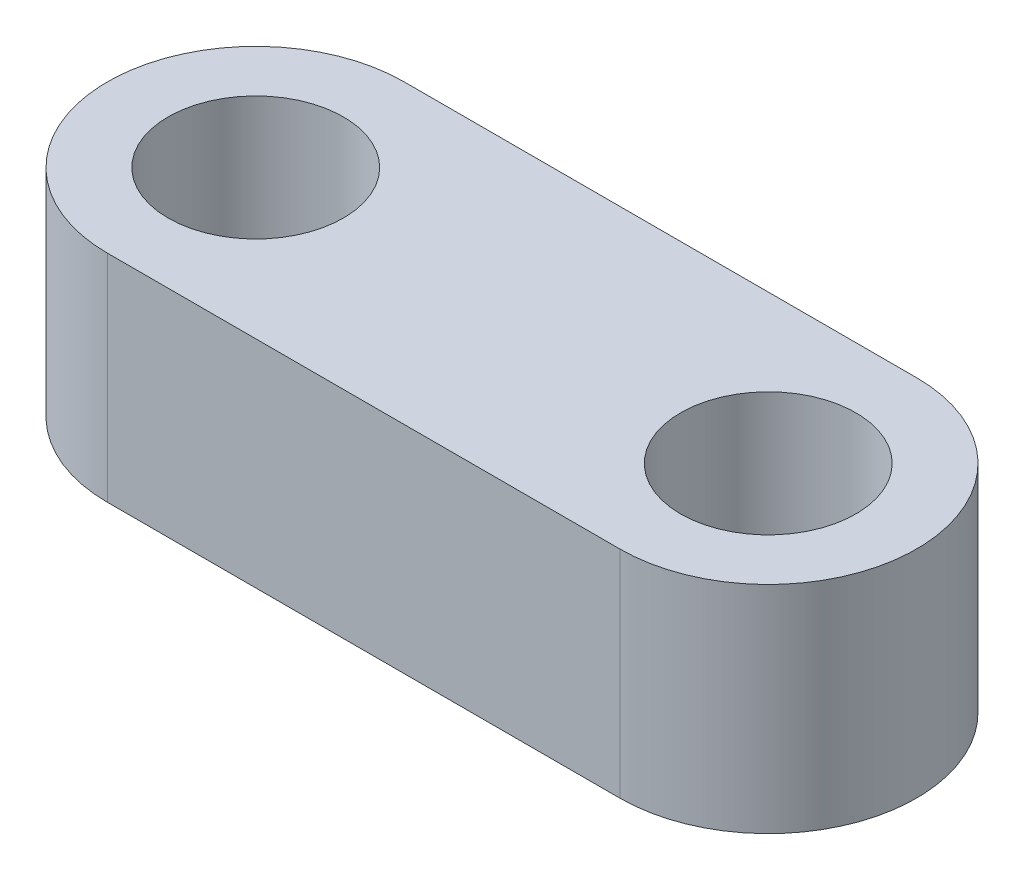
SolidWorks part; units mm, degrees
ref_plane "Front Plane" through (0, 0, 0) normal (0, 0, 1) x (1, 0, 0)
ref_plane "Top Plane" through (0, 0, 0) normal (0, 1, 0) x (1, 0, 0)
ref_plane "Right Plane" through (0, 0, 0) normal (1, 0, 0) x (0, 0, -1)
sketch "Sketch1" plane through (0, 0, 0) normal (0, 1, 0) x (1, 0, 0)
  line L0 (0, 0) -> (9.5, 0) construction
  line L1 (0, 2.75) -> (9.5, 2.75)
  line L2 (0, -2.75) -> (9.5, -2.75)
  arc A0 (0, 2.75) -> (0, -2.75) centre (0, 0) ccw
  arc A1 (9.5, -2.75) -> (9.5, 2.75) centre (9.5, 0) ccw
  circle A2 centre (0, 0) radius 1.625
  circle A3 centre (9.5, 0) radius 1.625
  dimension "D2" = 5.5
  dimension "D3" = 3.25
  dimension "D1" = 9.5
extrude "Boss-Extrude1" add sketch "Sketch1" along normal blind 4
sketch "Sketch2" plane through (0, 0, 0) normal (0, 1, 0) x (1, 0, 0)
  circle A0 centre (9.5, 0) radius 1.5
  dimension "D1" = 3
